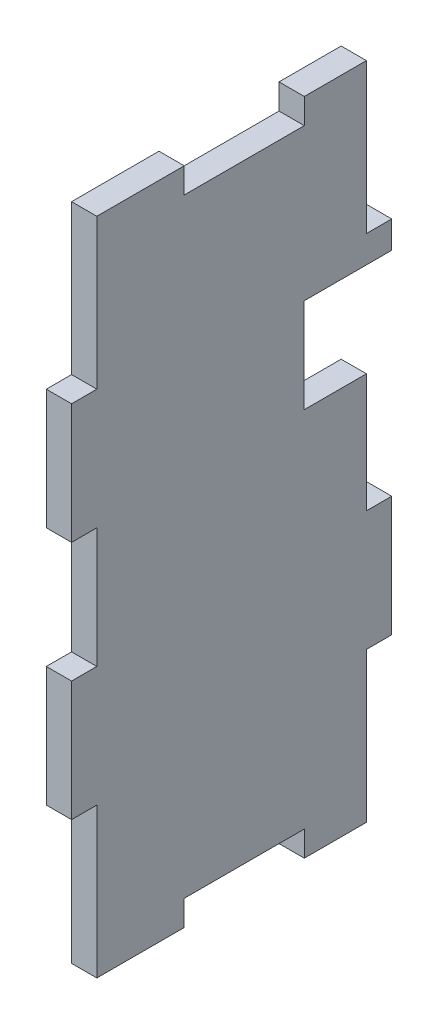
SolidWorks part; units mm, degrees
ref_plane "Front Plane" through (0, 0, 0) normal (0, 0, 1) x (1, 0, 0)
ref_plane "Top Plane" through (0, 0, 0) normal (0, 1, 0) x (1, 0, 0)
ref_plane "Right Plane" through (0, 0, 0) normal (1, 0, 0) x (0, 0, -1)
sketch "Sketch1" plane through (0, 0, 0) normal (1, 0, 0) x (0, 0, -1)
  line L122 (-18.5579, 36.9831) -> (-18.5579, 19.2081)
  line L123 (-18.5579, 19.2081) -> (-21.5579, 19.2081)
  line L124 (-21.5579, 19.2081) -> (-21.5579, 4.9581)
  line L125 (-21.5579, 4.9581) -> (-18.5579, 4.9581)
  line L126 (-18.5579, 4.9581) -> (-18.5579, -9.2919)
  line L127 (-18.5579, -9.2919) -> (-21.5579, -9.2919)
  line L128 (-21.5579, -9.2919) -> (-21.5579, -23.5419)
  line L129 (-21.5579, -23.5419) -> (-18.5579, -23.5419)
  line L130 (-18.5579, -23.5419) -> (-18.5579, -37.7919)
  line L131 (-18.5579, -37.7919) -> (-18.5579, -41.3169)
  line L132 (-18.5579, -41.3169) -> (-8.1829, -41.3169)
  line L133 (-8.1829, -41.3169) -> (-8.1829, -38.3169)
  line L134 (-8.1829, -38.3169) -> (6.0671, -38.3169)
  line L135 (6.0671, -38.3169) -> (6.0671, -41.3169)
  line L136 (6.0671, -41.3169) -> (13.4421, -41.3169)
  line L137 (13.4421, -41.3169) -> (13.4421, -23.5419)
  line L138 (13.4421, -23.5419) -> (16.4421, -23.5419)
  line L139 (16.4421, -23.5419) -> (16.4421, -9.2919)
  line L140 (16.4421, -9.2919) -> (13.4421, -9.2919)
  line L141 (13.4421, -9.2919) -> (13.4421, 4.9581)
  line L142 (13.4421, 4.9581) -> (16.4421, 4.9581)
  line L143 (16.4421, 4.9581) -> (16.4421, 19.2081)
  line L144 (16.4421, 19.2081) -> (13.4421, 19.2081)
  line L145 (13.4421, 19.2081) -> (13.4421, 33.4581)
  line L146 (13.4421, 33.4581) -> (13.4421, 36.9831)
  line L147 (13.4421, 36.9831) -> (6.0671, 36.9831)
  line L148 (6.0671, 36.9831) -> (6.0671, 33.9831)
  line L149 (6.0671, 33.9831) -> (-8.1829, 33.9831)
  line L150 (-8.1829, 33.9831) -> (-8.1829, 36.9831)
  line L151 (-8.1829, 36.9831) -> (-18.5579, 36.9831)
  dimension "D1" = 7.375
extrude "Boss-Extrude1" add sketch "Sketch1" along normal blind 3
sketch "Sketch2" plane through (3, 0, 0) normal (1, 0, 0) x (0, 0, -1)
  line L0 (13.4421, 36.9831) -> (6.0671, 36.9831) construction
  line L1 (6.0455, 15.9831) -> (17.0455, 15.9831)
  line L2 (6.0455, 15.9831) -> (6.0455, 4.791)
  line L3 (6.0455, 4.791) -> (17.0455, 4.791)
  line L4 (17.0455, 15.9831) -> (17.0455, 4.791)
  dimension "D1" = 21
  dimension "D2" = 11
extrude "Cut-Extrude1" cut sketch "Sketch2" against normal blind 10
